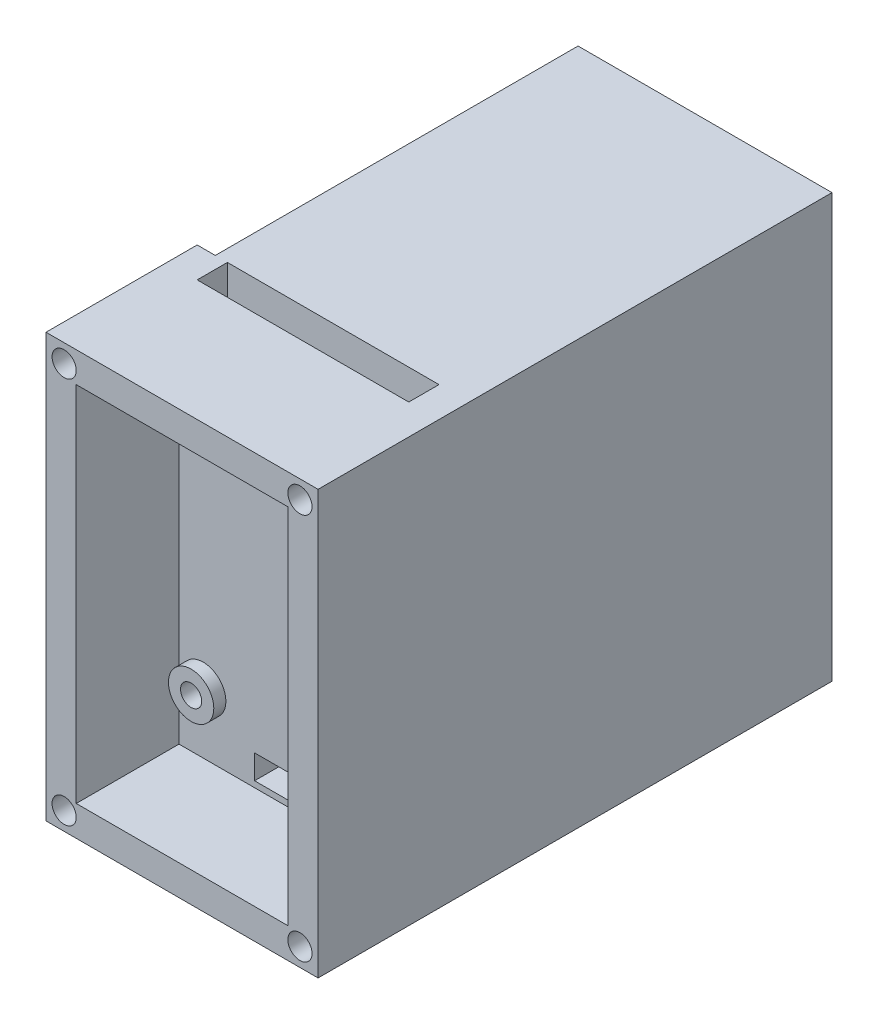
SolidWorks part; units mm, degrees
ref_plane "Přední rovina" through (0, 0, 0) normal (0, 0, 1) x (1, 0, 0)
ref_plane "Horní rovina" through (0, 0, 0) normal (0, 1, 0) x (1, 0, 0)
ref_plane "Pravá rovina" through (0, 0, 0) normal (1, 0, 0) x (0, 0, -1)
sketch "Skica1" plane through (0, 0, 0) normal (0, 0, 1) x (1, 0, 0)
  line L1 (0, 0) -> (35, 0)
  line L2 (0, 0) -> (0, 60)
  line L3 (0, 60) -> (35, 60)
  line L4 (35, 0) -> (35, 60)
  dimension "D1" = 35
  dimension "D2" = 60
extrude "Přidat vysunutím1" add sketch "Skica1" along normal blind 3
sketch "Skica3" plane through (0, 0, 0) normal (0, 0, -1) x (-1, 0, 0)
  line L1 (-35, 60) -> (0, 60)
  line L2 (-35, 60) -> (-35, 0)
  line L3 (-35, 0) -> (0, 0)
  line L4 (0, 60) -> (0, 0)
extrude "Vysunout tenkostěnný1" add sketch "Skica3" against normal blind 20 thin thin type one direction wall 5
sketch "Skica4" plane through (0, 0, 3) normal (0, 0, 1) x (1, 0, 0)
  line L0 (35, 60) -> (0, 60) construction
  line L1 (0, 60) -> (0, 0) construction
  line L2 (31, 55) -> (4, 55) construction
  line L3 (35, 60) -> (35, 0) construction
  line L4 (35, 0) -> (0, 0) construction
  line L5 (0, 0) -> (0, 60) construction
  line L6 (4, 10) -> (31, 10) construction
  line L7 (31, 10) -> (31, 55) construction
  line L8 (35, 0) -> (35, 60) construction
  line L9 (0, 0) -> (35, 0) construction
  line L10 (4, 55) -> (4, 10) construction
  circle A0 centre (4, 55) radius 1.75
  circle A1 centre (31, 55) radius 1.75
  circle A2 centre (31, 10) radius 1.75
  circle A3 centre (4, 10) radius 1.75
  dimension "D1" = 3.5
  dimension "D2" = 5
  dimension "D7" = 27
  dimension "D8" = 4
  dimension "D9" = 10
  dimension "D10" = 27
  dimension "D11" = 10
  dimension "D12" = 4
  dimension "D3" = 4
  dimension "D4" = 2
  dimension "D5" = 2
extrude "Vysunout tenkostěnný2" add sketch "Skica4" along normal blind 2 thin
sketch "Skica5" plane through (0, 0, 3) normal (0, 0, 1) x (1, 0, 0)
  circle A0 centre (4, 55) radius 1.75
  circle A1 centre (31, 55) radius 1.75
  circle A2 centre (31, 10) radius 1.75
  circle A3 centre (4, 10) radius 1.75
  circle A4 centre (4, 10) radius 1.75 construction
  circle A5 centre (31, 10) radius 1.75 construction
  circle A6 centre (31, 55) radius 1.75 construction
  circle A7 centre (4, 55) radius 1.75 construction
  circle A8 centre (4, 55) radius 1.75 construction
extrude "Odebrat vysunutím1" cut sketch "Skica5" against normal blind 1.5
sketch "Skica10" plane through (0, 0, 0) normal (0, 0, -1) x (-1, 0, 0)
  line L0 (-40, 65) -> (-40, -5) construction
  line L1 (5, -5) -> (-40, -5)
  line L2 (5, -5) -> (5, 65)
  line L3 (5, 65) -> (-40, 65)
  line L4 (-40, -5) -> (-40, 65)
  point P7 (0, 0)
extrude "Přidat vysunutím2" add sketch "Skica10" along normal blind 5
sketch "Skica12" plane through (0, 0, -5) normal (0, 0, -1) x (-1, 0, 0)
  line L0 (-40, 65) -> (-40, -5) construction
  line L1 (5, 65) -> (-40, 65)
  line L2 (5, 65) -> (5, 14.1599)
  line L3 (5, 14.1599) -> (-40, 14.1599)
  line L4 (-40, 65) -> (-40, 14.1599)
  line L6 (0, 65) -> (-35, 65)
  line L7 (0, 65) -> (0, 14.1599)
  line L8 (0, 14.1599) -> (-35, 14.1599)
  line L9 (-35, 65) -> (-35, 14.1599)
  point P11 (0, 0)
  dimension "D1" = 5
  dimension "D2" = 5
extrude "Odebrat vysunutím5" cut sketch "Skica12" against normal blind 5 contours L1 L9 L3 L7
sketch "Skica13" plane through (0, 0, -5) normal (0, 0, -1) x (-1, 0, 0)
  line L1 (-40, 65) -> (5, 65)
  line L2 (-40, 65) -> (-40, -5)
  line L3 (-40, -5) -> (5, -5)
  line L4 (5, 65) -> (5, -5)
extrude "Přidat vysunutím3" add sketch "Skica13" along normal blind 5
sketch "Skica16" plane through (0, 0, -10) normal (0, 0, -1) x (-1, 0, 0)
  line L0 (-40, 65) -> (-40, -5) construction
  line L1 (5, -5) -> (-40, -5)
  line L2 (5, -5) -> (5, 0)
  line L3 (5, 0) -> (-35, 0)
  line L4 (-40, -5) -> (-40, -2)
  line L5 (5, -5) -> (5, 65) construction
  line L6 (-40, 65) -> (-37, 65)
  line L7 (-40, 65) -> (-40, -5)
  line L8 (-40, -5) -> (-37, -5)
  line L9 (-35, 60) -> (-35, 0)
  line L10 (-40, 65) -> (5, 65)
  line L11 (-40, 65) -> (-40, 62)
  line L12 (-35, 60) -> (5, 60)
  line L13 (5, 65) -> (5, 60)
  line M1 (-40, 65) -> (-40, -5)
  line M2 (-40, -5) -> (5, -5)
  line M3 (5, -5) -> (5, 65)
  line M4 (5, 65) -> (-40, 65)
  dimension "D1" = 5
  dimension "D2" = 5
  dimension "D3" = 5
extrude "Přidat vysunutím5" add sketch "Skica16" along normal blind 50 contours L9 L12 L7 L1 L3 M3 M4 M1 M2
sketch "Skica17" plane through (0, 0, -60) normal (0, 0, -1) x (-1, 0, 0)
  line L1 (-40, 65) -> (5, 65)
  line L2 (-40, 65) -> (-40, -5)
  line L3 (-40, -5) -> (5, -5)
  line L4 (5, 65) -> (5, -5)
extrude "Přidat vysunutím6" add sketch "Skica17" along normal blind 5
sketch "Skica7" plane through (0, 0, 20) normal (0, 0, 1) x (1, 0, 0)
  line L0 (40, 65) -> (40, -5) construction
  line L1 (-5, 65) -> (40, 65) construction
  line L2 (37, 62) -> (-2, 62) construction
  line L3 (37, 62) -> (37, -2) construction
  line L5 (-2, 62) -> (-2, -2) construction
  line L6 (-2, -2) -> (37, -2) construction
  line L7 (40, -5) -> (-5, -5) construction
  line L8 (-5, -5) -> (-5, 65) construction
  circle A0 centre (37, 62) radius 2
  circle A1 centre (-2, 62) radius 2
  circle A2 centre (-2, -2) radius 2
  circle A3 centre (37, -2) radius 2
  dimension "D1" = 3
  dimension "D2" = 3
  dimension "D3" = 4
  dimension "D8" = 3
  dimension "D9" = 3
  dimension "D10" = 3
  dimension "D11" = 3
  dimension "D6" = 39
  dimension "D7" = 64
  dimension "D4" = 2
  dimension "D5" = 2
extrude "Odebrat vysunutím3" cut sketch "Skica7" against normal blind 3.2
sketch "Skica8" plane through (0, 0, 3) normal (0, 0, 1) x (1, 0, 0)
  line L0 (0, 0) -> (35, 0) construction
  line L1 (12.5, 1) -> (22.5, 1)
  line L2 (12.5, 1) -> (12.5, 5)
  line L3 (12.5, 5) -> (22.5, 5)
  line L4 (22.5, 1) -> (22.5, 5)
  line L5 (0, 60) -> (0, 0) construction
  dimension "D1" = 4
  dimension "D2" = 10
  dimension "D3" = 1
  dimension "D4" = 12.5
extrude "Odebrat vysunutím6" cut sketch "Skica8" against normal up to next
sketch "Skica21" plane through (-5, 0, 0) normal (-1, 0, 0) x (0, 0, 1)
  line L0 (20, -5) -> (-65, -5) construction
  line L1 (-65, 65) -> (-5, 65)
  line L2 (-65, 65) -> (-65, -5)
  line L3 (-65, -5) -> (-5, -5)
  line L4 (-5, 65) -> (-5, -5)
  line L5 (-10, 0) -> (-10, 60) construction
  dimension "D1" = 5
extrude "Odebrat vysunutím7" cut sketch "Skica21" against normal blind 3
sketch "Skica22" plane through (-2, 0, 0) normal (-1, 0, 0) x (0, 0, 1)
  line L0 (-65, 65) -> (-65, -5) construction
  line L1 (-5, 65) -> (-65, 65) construction
  line L2 (-65, -5) -> (-5, -5) construction
  line L3 (-5, -5) -> (-5, 65) construction
  circle A0 centre (-7.5, 62.5) radius 1.75
  circle A1 centre (-7.5, -2.5) radius 1.75
  circle A2 centre (-62.5, -2.5) radius 1.75
  circle A3 centre (-62.5, 62.5) radius 1.75
  point P8 (0, 0)
  point P9 (0, 0)
  point P10 (0, 0)
  point P11 (0, 0)
  point P16 (0, 0)
  point P17 (-60.5, -2.0505)
  point P18 (0, 0)
  point P23 (-63, -0.959)
  dimension "D3" = 3.5
  dimension "D1" = 2.5
  dimension "D2" = 2.5
  dimension "D4" = 2.5
  dimension "D5" = 2.5
extrude "Odebrat vysunutím8" cut sketch "Skica22" against normal blind 5
sketch "Skica23" plane through (0, -5, 0) normal (0, -1, 0) x (1, 0, 0)
  line L0 (40, 20) -> (40, -65) construction
  line L1 (40, -65) -> (-2, -65) construction
  circle A0 centre (14.5, -45.9234) radius 5
  dimension "D1" = 10
  dimension "D2" = 25.5
  dimension "D3" = 19.0766
extrude "Odebrat vysunutím9" cut sketch "Skica23" against normal blind 5
